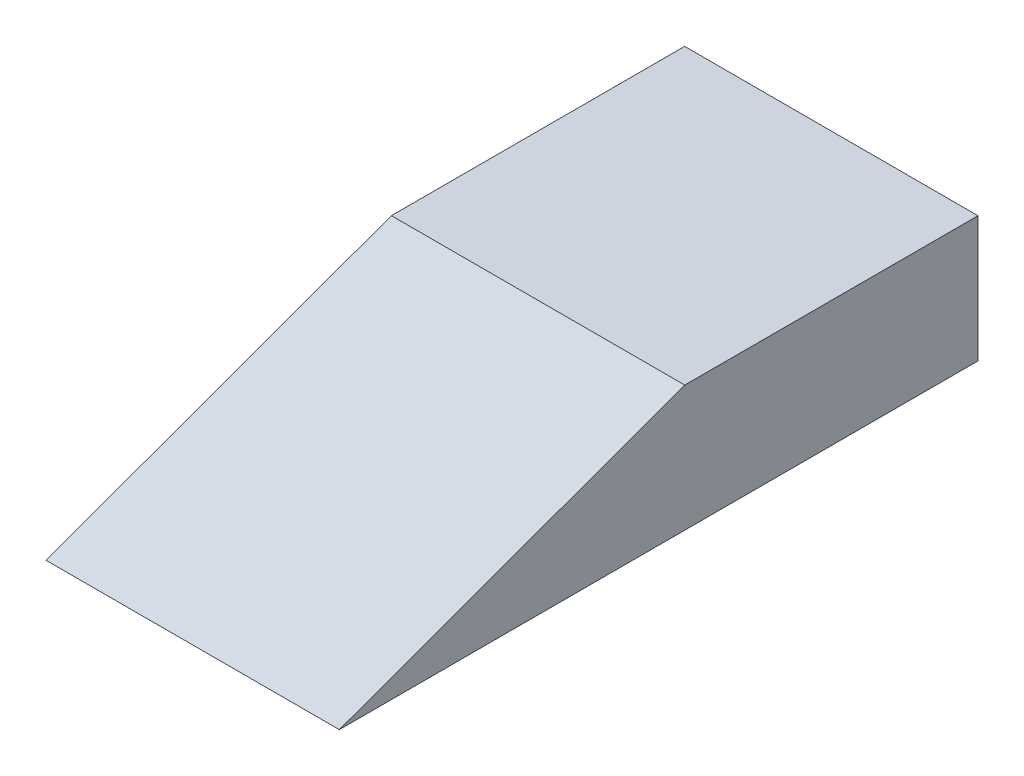
SolidWorks part; units mm, degrees
ref_plane "Front Plane" through (0, 0, 0) normal (0, 0, 1) x (1, 0, 0)
ref_plane "Top Plane" through (0, 0, 0) normal (0, 1, 0) x (1, 0, 0)
ref_plane "Right Plane" through (0, 0, 0) normal (1, 0, 0) x (0, 0, -1)
sketch "Sketch1" plane through (0, 0, 0) normal (1, 0, 0) x (0, 0, -1)
  line L0 (-202.7508, -88.0536) -> (209.2492, -88.0536)
  line L1 (209.2492, 61.9021) -> (209.2492, 61.9464)
  line L2 (209.2492, 61.9464) -> (209.3708, 61.9464)
  line L3 (209.3708, 61.9464) -> (-202.7508, -88.0536)
  line L4 (209.2492, 61.9464) -> (559.2492, 61.9464)
  line L5 (559.2492, 61.9464) -> (559.2492, -88.0536)
  line L6 (559.2492, -88.0536) -> (209.2492, -88.0536)
  dimension "D1" = 412
  dimension "D2" = 150
  dimension "D3" = 20
  dimension "D4" = 350
  dimension "D5" = 209.2492
  dimension "D6" = 88.0536
  dimension "D7" = 438.5707
extrude "Boss-Extrude1" add sketch "Sketch1" along normal blind 350 contours L6 L5 L4 L3 L0
